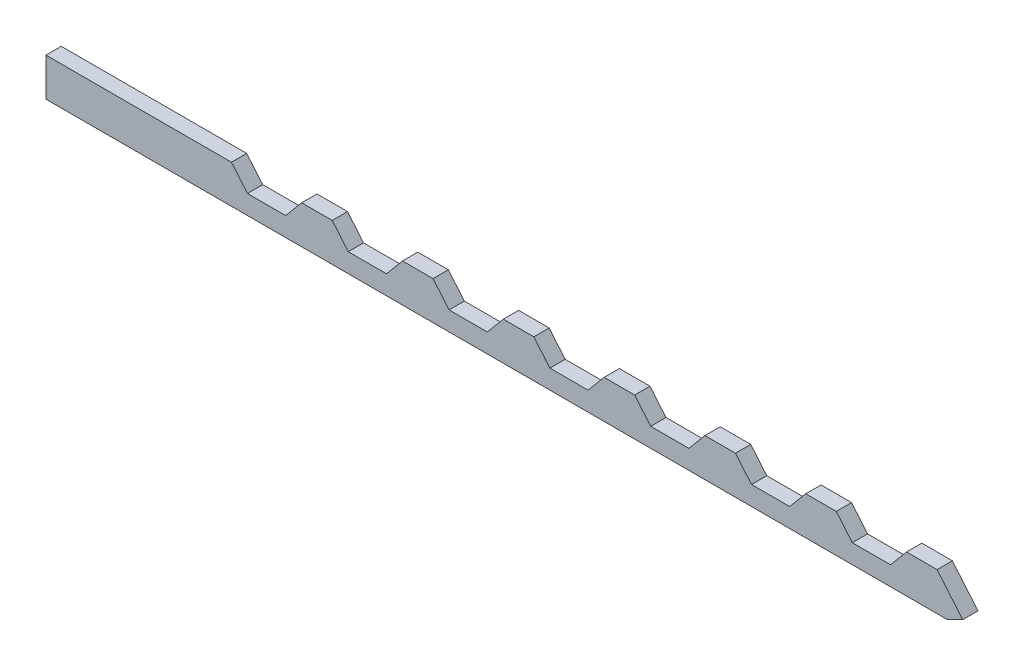
SolidWorks part; units mm, degrees
ref_plane "Front Plane" through (0, 0, 0) normal (0, 0, 1) x (1, 0, 0)
ref_plane "Top Plane" through (0, 0, 0) normal (0, 1, 0) x (1, 0, 0)
ref_plane "Right Plane" through (0, 0, 0) normal (1, 0, 0) x (0, 0, -1)
other "Bounding Box"
ref_plane "Default Plane" through (-8.9266, -12.7485, 0) normal (-0.1736, 0.9848, 0) x (0.9848, 0.1736, 0)
sketch "Sketch1" plane through (0, 0, 0) normal (0, 0, 1) x (1, 0, 0)
  line L1 (152.4, -6.35) -> (-152.4, -6.35)
  line L2 (152.4, -6.35) -> (152.4, 6.35)
  line L3 (152.4, 6.35) -> (-152.4, 6.35)
  line L4 (-152.4, -6.35) -> (-152.4, 6.35)
  line L5 (152.4, -6.35) -> (-152.4, 6.35) construction
  line L6 (152.4, 6.35) -> (-152.4, -6.35) construction
  point P0 (0, 0)
  dimension "D1" = 12.7
  dimension "D2" = 304.8
extrude "Boss-Extrude1" add sketch "Sketch1" along normal blind 5.08
sketch "Sketch2" plane through (0, 0, 5.08) normal (0, 0, 1) x (1, 0, 0)
  line L0 (-152.4, 6.35) -> (-152.4, -6.35) construction
  line L1 (152.4, -6.35) -> (152.4, 6.35) construction
  line L3 (-152.4, -6.35) -> (152.4, -6.35) construction
  line L4 (-152.4, 6.35) -> (-152.4, -6.35)
  line L5 (152.4, -6.35) -> (152.4, 6.35)
  line L7 (-152.4, -6.35) -> (152.4, -6.35)
  line L8 (115.6865, 0) -> (110.3582, 6.35)
  line L9 (143.8747, 6.35) -> (152.4, -3.81)
  line L10 (143.8747, 6.35) -> (133.7147, 6.35)
  line L11 (133.7147, 6.35) -> (128.3865, 0)
  line L12 (128.3865, 0) -> (115.6865, 0)
  line L13 (110.3582, 6.35) -> (100.1982, 6.35)
  line L14 (100.1982, 6.35) -> (94.8699, 0)
  line L15 (94.8699, 0) -> (82.1699, 0)
  line L16 (82.1699, 0) -> (76.8416, 6.35)
  line L17 (76.8416, 6.35) -> (66.6816, 6.35)
  line L18 (66.6816, 6.35) -> (61.3533, 0)
  line L19 (61.3533, 0) -> (48.6533, 0)
  line L20 (48.6533, 0) -> (43.3251, 6.35)
  line L21 (43.3251, 6.35) -> (33.1651, 6.35)
  line L22 (33.1651, 6.35) -> (27.8368, 0)
  line L23 (27.8368, 0) -> (15.1368, 0)
  line L24 (9.8085, 6.35) -> (15.1368, 0)
  line L25 (9.8085, 6.35) -> (-0.3515, 6.35)
  line L26 (-0.3515, 6.35) -> (-5.6798, 0)
  line L27 (-5.6798, 0) -> (-18.3798, 0)
  line L28 (-18.3798, 0) -> (-23.7081, 6.35)
  line L29 (-23.7081, 6.35) -> (-33.8681, 6.35)
  line L30 (-33.8681, 6.35) -> (-39.1964, 0)
  line L31 (-39.1964, 0) -> (-51.8964, 0)
  line L32 (-57.2246, 6.35) -> (-51.8964, 0)
  line L33 (-57.2246, 6.35) -> (-67.3846, 6.35)
  line L34 (-67.3846, 6.35) -> (-72.7129, 0)
  line L35 (-72.7129, 0) -> (-85.4129, 0)
  line L36 (133.7147, 6.35) -> (143.8747, 6.35)
  line L37 (152.4, 0) -> (-152.4, 0) construction
  line L38 (152.4, 6.35) -> (-152.4, 6.35) construction
  line L39 (152.4, -3.81) -> (147.32, -6.35)
  line L40 (-90.7412, 6.35) -> (-85.4129, 0)
  line L41 (-90.7412, 6.35) -> (-100.9012, 6.35)
  line M41 (152.4, -6.35) -> (152.4, 6.35)
  line M42 (152.4, 6.35) -> (-152.4, 6.35)
  dimension "D1" = 10.16
  dimension "D2" = 130
  dimension "D3" = 130
  dimension "D4" = 12.7
  dimension "D6" = 130
  dimension "D7" = 10.16
  dimension "D8" = 5.08
extrude "Cut-Extrude1" cut sketch "Sketch2" against normal through all contours L12 L11 L8 M42 | L37 L9 M41 M42 | L5 L37 L9 | L39 L7 M41 | L16 L15 L14 M42 | L20 L19 L18 M42 | L24 L23 L22 M42 | L28 L27 L26 M42 | L32 L31 L30 M42 | L40 L35 L34 M42
